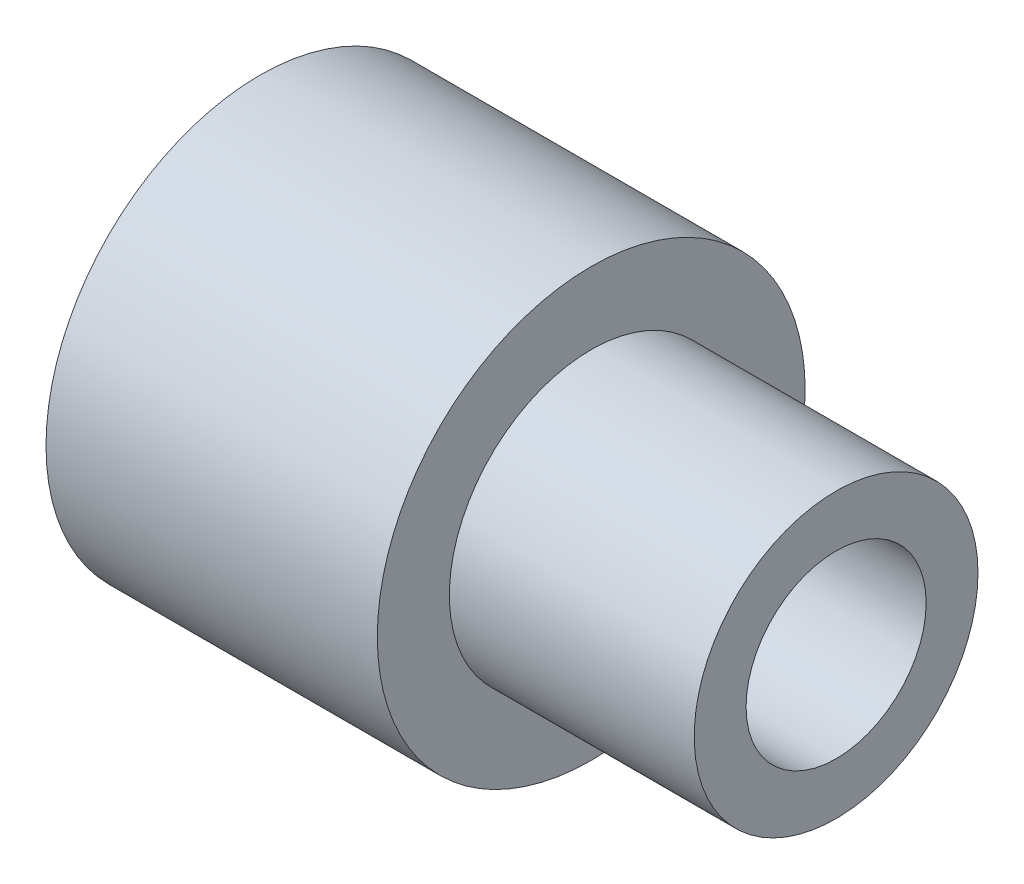
SolidWorks part; units mm, degrees
ref_plane "Front Plane" through (0, 0, 0) normal (0, 0, 1) x (1, 0, 0)
ref_plane "Top Plane" through (0, 0, 0) normal (0, 1, 0) x (1, 0, 0)
ref_plane "Right Plane" through (0, 0, 0) normal (1, 0, 0) x (0, 0, -1)
sketch "Sketch1" plane through (0, 0, 0) normal (1, 0, 0) x (0, 0, -1)
  circle A0 centre (0, 0) radius 3.7719
  dimension "D1" = 7.5438
extrude "Boss-Extrude1" add sketch "Sketch1" along normal blind 5.842
sketch "Sketch2" plane through (5.842, 0, 0) normal (1, 0, 0) x (0, 0, -1)
  circle A0 centre (0, 0) radius 2.5019
  dimension "D1" = 5.0038
extrude "Boss-Extrude2" add sketch "Sketch2" along normal blind 4.318
sketch "Sketch3" plane through (10.16, 0, 0) normal (1, 0, 0) x (0, 0, -1)
  circle A0 centre (0, 0) radius 1.5875
  dimension "D1" = 3.175
extrude "Cut-Extrude1" cut sketch "Sketch3" against normal through all
